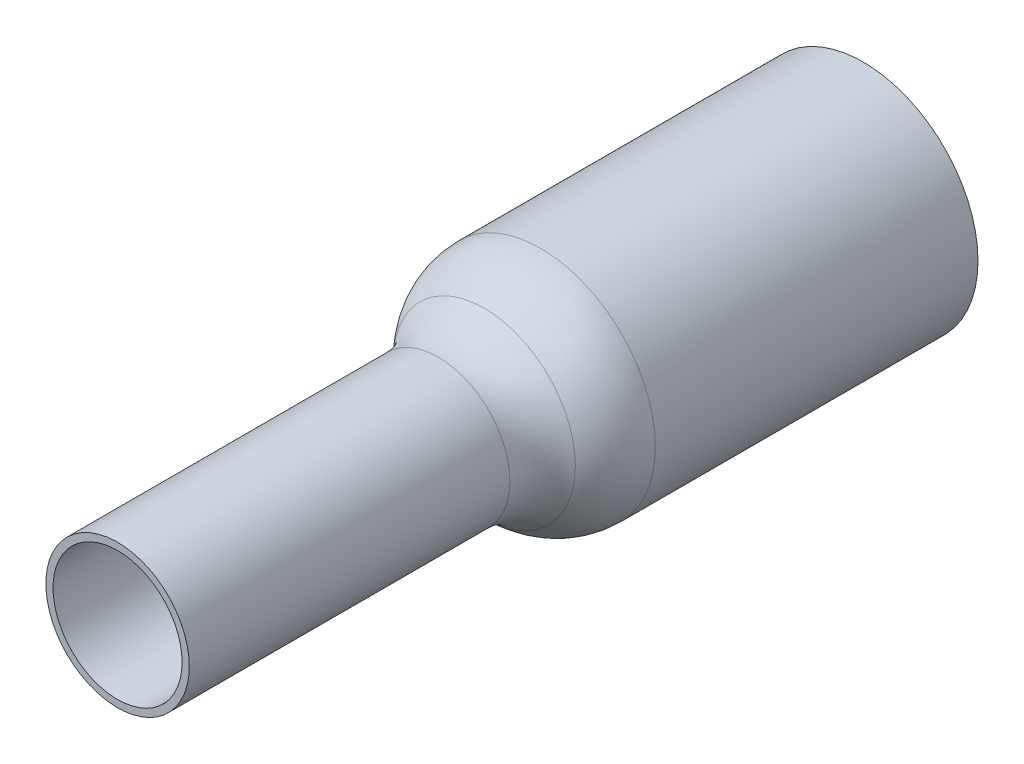
SolidWorks part; units mm, degrees
material "NBR"
ref_plane "Front Plane" through (0, 0, 0) normal (0, 0, 1) x (1, 0, 0)
ref_plane "Top Plane" through (0, 0, 0) normal (0, 1, 0) x (1, 0, 0)
ref_plane "Right Plane" through (0, 0, 0) normal (1, 0, 0) x (0, 0, -1)
sketch "Sketch1" plane through (0, 0, 0) normal (1, 0, 0) x (0, 0, -1)
  line L0 (0, 0) -> (10.4, 0) construction
  line L1 (0, 0.9) -> (4.4717, 0.9)
  line L2 (5.9, 1.5) -> (10.4, 1.5)
  arc A0 (4.4717, 0.9) -> (5.1859, 1.2) centre (4.4717, 1.9) ccw
  arc A1 (5.1859, 1.2) -> (5.9, 1.5) centre (5.9, 0.5) cw
  dimension "D1" = 4.5
  dimension "D5" = 1
  dimension "D2" = 3
  dimension "D3" = 1.8
  dimension "D4" = 10.4
revolve "Revolve-Thin1" add sketch "Sketch1" angle 360 about L0 wall 0.1
equation "\"panjang\"= 120"
equation "\"lebar\"=40"
equation "\"tinggi\"=10"
